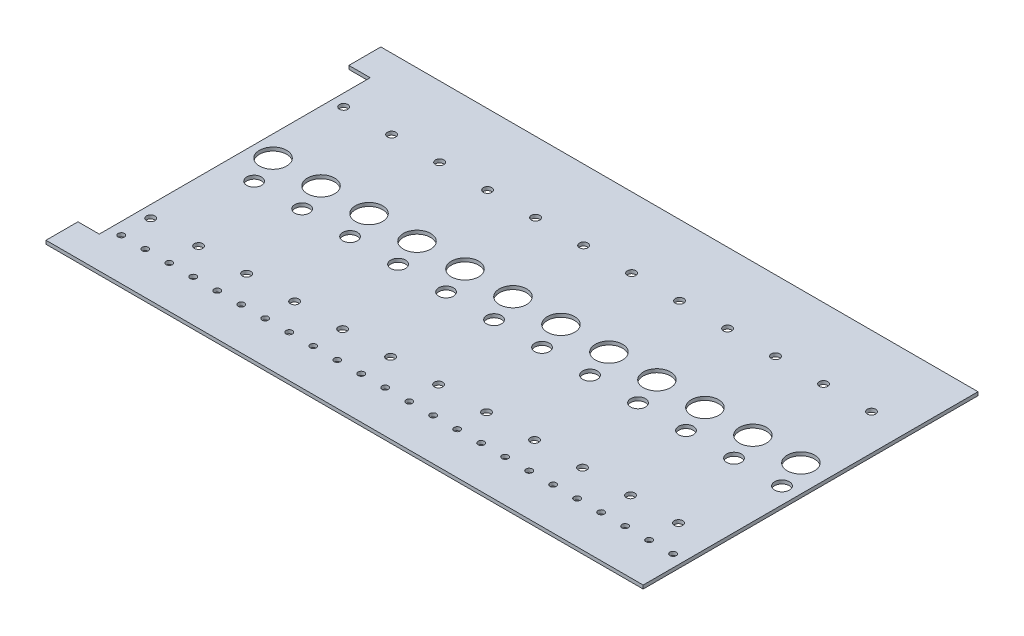
SolidWorks part; units mm, degrees
ref_plane "Front Plane" through (0, 0, 0) normal (0, 0, 1) x (1, 0, 0)
ref_plane "Top Plane" through (0, 0, 0) normal (0, 1, 0) x (1, 0, 0)
ref_plane "Right Plane" through (0, 0, 0) normal (1, 0, 0) x (0, 0, -1)
sketch "Sketch1" plane through (0, 0, 0) normal (0, 1, 0) x (1, 0, 0)
  line L1 (0, 0) -> (137.2499, 0)
  line L2 (0, 0) -> (0, 79.8044)
  line L3 (0, 79.8044) -> (137.2499, 79.8044)
  line L4 (137.2499, 0) -> (137.2499, 79.8044)
  circle A0 centre (2.8594, 10) radius 0.75
  circle A1 centre (8.5781, 10) radius 0.75
  circle A2 centre (14.2968, 10) radius 0.75
  circle A3 centre (20.0156, 10) radius 0.75
  circle A4 centre (25.7343, 10) radius 0.75
  circle A5 centre (31.453, 10) radius 0.75
  circle A6 centre (37.1718, 10) radius 0.75
  circle A7 centre (42.8905, 10) radius 0.75
  circle A8 centre (48.6092, 10) radius 0.75
  circle A9 centre (54.328, 10) radius 0.75
  circle A10 centre (60.0467, 10) radius 0.75
  circle A11 centre (65.7654, 10) radius 0.75
  circle A12 centre (71.4842, 10) radius 0.75
  circle A13 centre (77.2029, 10) radius 0.75
  circle A14 centre (82.9216, 10) radius 0.75
  circle A15 centre (88.6404, 10) radius 0.75
  circle A16 centre (94.3591, 10) radius 0.75
  circle A17 centre (100.0778, 10) radius 0.75
  circle A18 centre (105.7966, 10) radius 0.75
  circle A19 centre (111.5153, 10) radius 0.75
  circle A20 centre (117.234, 10) radius 0.75
  circle A21 centre (122.9528, 10) radius 0.75
  circle A22 centre (128.6715, 10) radius 0.75
  circle A23 centre (134.3903, 10) radius 0.75
  circle A24 centre (2.8594, 17) radius 1
  circle A25 centre (14.2969, 17) radius 1
  circle A26 centre (25.7344, 17) radius 1
  circle A27 centre (37.1719, 17) radius 1
  circle A28 centre (48.6093, 17) radius 1
  circle A29 centre (60.0468, 17) radius 1
  circle A30 centre (71.4843, 17) radius 1
  circle A31 centre (82.9218, 17) radius 1
  circle A32 centre (94.3593, 17) radius 1
  circle A33 centre (105.7968, 17) radius 1
  circle A34 centre (117.2343, 17) radius 1
  circle A35 centre (128.6718, 17) radius 1
  circle A36 centre (7.5223, 37) radius 1.75
  circle A37 centre (18.9598, 37) radius 1.75
  circle A38 centre (30.3973, 37) radius 1.75
  circle A39 centre (41.8348, 37) radius 1.75
  circle A40 centre (53.2723, 37) radius 1.75
  circle A41 centre (64.7097, 37) radius 1.75
  circle A42 centre (76.1472, 37) radius 1.75
  circle A43 centre (87.5847, 37) radius 1.75
  circle A44 centre (99.0222, 37) radius 1.75
  circle A45 centre (110.4597, 37) radius 1.75
  circle A46 centre (121.8972, 37) radius 1.75
  circle A47 centre (133.3347, 37) radius 1.75
  circle A48 centre (5.0336, 44) radius 3.25
  circle A49 centre (16.4711, 44) radius 3.25
  circle A50 centre (27.9086, 44) radius 3.25
  circle A51 centre (39.3461, 44) radius 3.25
  circle A52 centre (50.7836, 44) radius 3.25
  circle A53 centre (62.2211, 44) radius 3.25
  circle A54 centre (73.6586, 44) radius 3.25
  circle A55 centre (85.0961, 44) radius 3.25
  circle A56 centre (96.5336, 44) radius 3.25
  circle A57 centre (107.971, 44) radius 3.25
  circle A58 centre (119.4085, 44) radius 3.25
  circle A59 centre (130.846, 44) radius 3.25
  circle A60 centre (2.8594, 63) radius 1
  circle A61 centre (14.2969, 63) radius 1
  circle A62 centre (25.7344, 63) radius 1
  circle A63 centre (37.1719, 63) radius 1
  circle A64 centre (48.6093, 63) radius 1
  circle A65 centre (60.0468, 63) radius 1
  circle A66 centre (71.4843, 63) radius 1
  circle A67 centre (82.9218, 63) radius 1
  circle A68 centre (94.3593, 63) radius 1
  circle A69 centre (105.7968, 63) radius 1
  circle A70 centre (117.2343, 63) radius 1
  circle A71 centre (128.6718, 63) radius 1
  dimension "D5" = 1.5
  dimension "D8" = 2
  dimension "D11" = 3.5
  dimension "D14" = 6.5
  dimension "D17" = 2
  dimension "D1" = 79.8044
  dimension "D2" = 137.2499
  dimension "D3" = 10
  dimension "D4" = 2.8594
  dimension "D7" = 17
  dimension "D10" = 37
  dimension "D13" = 44
  dimension "D16" = 63
  dimension "D6" = 24
  dimension "D9" = 12
  dimension "D12" = 12
  dimension "D15" = 12
  dimension "D18" = 12
extrude "Boss-Extrude1" add sketch "Sketch1" along normal blind 0.8382
sketch "Sketch2" plane through (0, 0, 0) normal (-1, 0, 0) x (0, 0, 1)
  line L0 (-79.8044, 0.8382) -> (0, 0.8382) construction
  line L1 (-79.8044, 0) -> (-72.1844, 0)
  line L2 (-79.8044, 0) -> (-79.8044, 0.8382)
  line L3 (-79.8044, 0.8382) -> (-72.1844, 0.8382)
  line L4 (-72.1844, 0) -> (-72.1844, 0.8382)
  line L6 (0, 0) -> (-7.62, 0)
  line L7 (0, 0) -> (0, 0.8382)
  line L8 (0, 0.8382) -> (-7.62, 0.8382)
  line L9 (-7.62, 0) -> (-7.62, 0.8382)
  dimension "D1" = 7.62
  dimension "D2" = 7.62
extrude "Boss-Extrude2" add sketch "Sketch2" along normal blind 5.08
